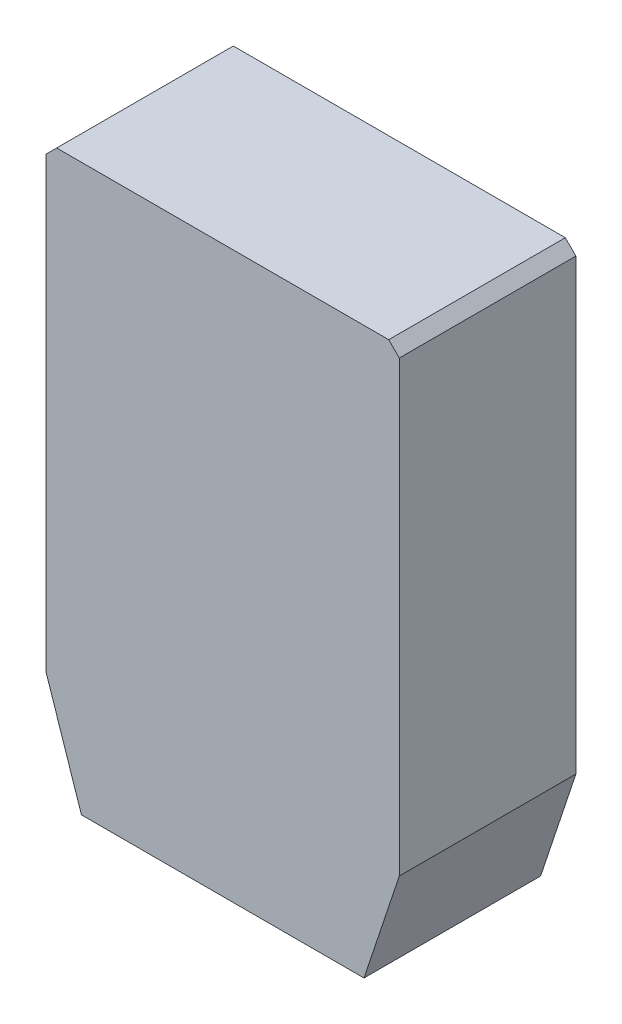
SolidWorks part; units mm, degrees
ref_plane "Front Plane" through (0, 0, 0) normal (0, 0, 1) x (1, 0, 0)
ref_plane "Top Plane" through (0, 0, 0) normal (0, 1, 0) x (1, 0, 0)
ref_plane "Right Plane" through (0, 0, 0) normal (1, 0, 0) x (0, 0, -1)
sketch "Sketch1" plane through (0, 0, 0) normal (0, 0, 1) x (1, 0, 0)
  line L0 (0, -80) -> (0, 80) construction
  line L1 (-47, 80) -> (47, 80)
  line L2 (47, 80) -> (50, 77)
  line L3 (50, 77) -> (50, -50)
  line L4 (50, -50) -> (40, -80)
  line L5 (40, -80) -> (-40, -80)
  line L6 (-50, -50) -> (-40, -80)
  line L7 (-50, 77) -> (-50, -50)
  line L8 (-47, 80) -> (-50, 77)
  point P4 (0, 0)
  dimension "D1" = 160
  dimension "D2" = 100
  dimension "D3" = 3
  dimension "D4" = 3
  dimension "D5" = 30
  dimension "D6" = 40
extrude "Boss-Extrude1" add sketch "Sketch1" along normal blind 50
